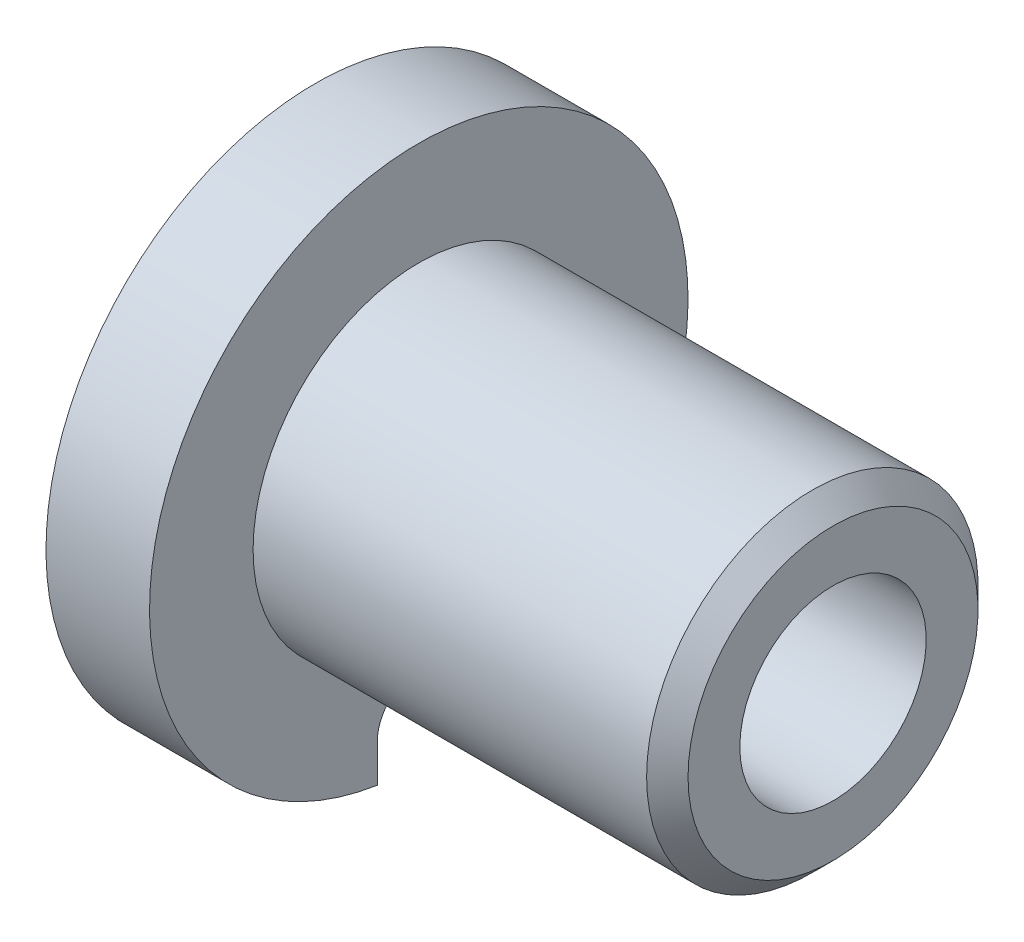
SolidWorks part; units mm, degrees
ref_plane "Plane1" through (0, 0, 0) normal (0, 0, 1) x (1, 0, 0)
ref_plane "Plane2" through (0, 0, 0) normal (0, 1, 0) x (1, 0, 0)
ref_plane "Plane3" through (0, 0, 0) normal (1, 0, 0) x (0, 0, -1)
sketch "Esquisse1" plane through (0, 0, 0) normal (0, 0, 1) x (1, 0, 0)
  line L0 (0, 0) -> (38.5536, 0) construction
  line L1 (0, 4.5) -> (25, 4.5)
  line L2 (25, 4.5) -> (25, 8)
  line L3 (25, 8) -> (5, 8)
  line L4 (5, 8) -> (5, 13)
  line L5 (5, 13) -> (0, 13)
  line L6 (0, 13) -> (0, 4.5)
  dimension "D1" = 8
  dimension "D2" = 4.5
  dimension "D3" = 20
  dimension "rayon_ext" = 13
  dimension "D5" = 25
revolve "Base-Révolution" add sketch "Esquisse1" angle 360 about L0
chamfer "Chanfrein2" distance 1 angle 45
sketch "Esquisse2" plane through (0, 0, 0) normal (-1, 0, 0) x (0, 0, 1)
  line L0 (0, 20.0822) -> (0, -15.0208) construction
  line L1 (-17.8029, 0) -> (22.8814, 0) construction
  line L2 (2, -11) -> (2, -12.8452)
  line L3 (-2, -11) -> (-2, -12.8452)
  arc A0 (2, -11) -> (-2, -11) centre (0, -11) ccw
  arc A1 (-2, -12.8452) -> (2, -12.8452) centre (0, 0) ccw
  dimension "D1" = 4
  dimension "diam_ext" = 26
  dimension "D2" = 11
extrude "Enlèv. mat.-Extru.1" cut sketch "Esquisse2" against normal through all
equation "\"diam_ext@Esquisse2\" = 2* \"rayon_ext@esquisse1\""
